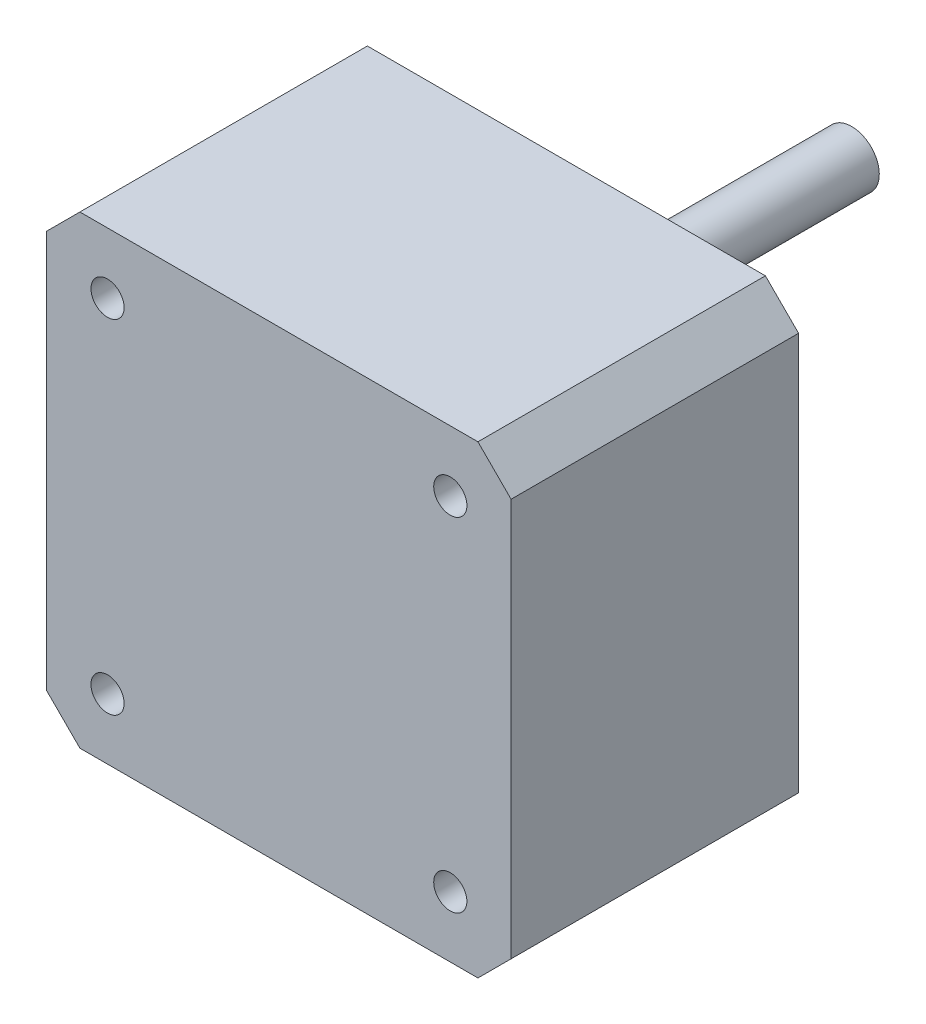
SolidWorks part; units mm, degrees
ref_plane "Front Plane" through (0, 0, 0) normal (0, 0, 1) x (1, 0, 0)
ref_plane "Top Plane" through (0, 0, 0) normal (0, 1, 0) x (1, 0, 0)
ref_plane "Right Plane" through (0, 0, 0) normal (1, 0, 0) x (0, 0, -1)
sketch "Sketch1" plane through (0, 0, 0) normal (0, 0, 1) x (1, 0, 0)
  line L1 (-21, 21) -> (21, 21)
  line L2 (-21, 21) -> (-21, -21)
  line L3 (-21, -21) -> (21, -21)
  line L4 (21, 21) -> (21, -21)
  line L5 (-21, 21) -> (21, -21) construction
  line L6 (-21, -21) -> (21, 21) construction
  point P0 (0, 0)
  dimension "D1" = 42
  dimension "D2" = 42
extrude "Boss-Extrude1" add sketch "Sketch1" along normal blind 26 contours L1 L4 L3 L2
chamfer "Chamfer1" distance 3 angle 45 4 edges at (21, -21, 13) (-21, -21, 13) (-21, 21, 13) (21, 21, 13)
sketch "Sketch4" plane through (0, 0, 0) normal (0, 0, -1) x (-1, 0, 0)
  circle A0 centre (0, 0) radius 11.25
  dimension "D1" = 22.5
extrude "Boss-Extrude2" add sketch "Sketch4" against normal blind 0.5
sketch "Sketch8" plane through (0, 0, 0) normal (0, 0, -1) x (-1, 0, 0)
  circle A4 centre (15.5, 15.5) radius 1.5
  circle A5 centre (-15.5, 15.5) radius 1.5
  circle A6 centre (-15.5, -15.5) radius 1.5
  circle A7 centre (15.5, -15.5) radius 1.5
  dimension "D1" = 31
  dimension "D2" = 31
  dimension "D4" = 3
  dimension "D3" = 15.5
  dimension "D5" = 15.5
extrude "Cut-Extrude4" cut sketch "Sketch8" against normal up to next
sketch "Sketch9" plane through (0, 0, 0) normal (0, 0, -1) x (-1, 0, 0)
  circle A0 centre (0, 0) radius 18.35
  dimension "D1" = 36.7
extrude "Cut-Extrude5" cut sketch "Sketch9" against normal blind 0.5
sketch "Sketch10" plane through (0, 0, 0.5) normal (0, 0, -1) x (-1, 0, 0)
  line L0 (18, 21) -> (-18, 21) construction
  circle A0 centre (0, 8.3) radius 8.9
  circle A3 centre (0, 8.3) radius 2.75
  dimension "D1" = 17.8
  dimension "D3" = 5.5
  dimension "D2" = 12.7
extrude "Boss-Extrude3" add sketch "Sketch10" along normal blind 3.5
sketch "Sketch11" plane through (0, 0, 0.5) normal (0, 0, -1) x (-1, 0, 0)
  line L0 (-1.6815, 6.45) -> (1.6815, 6.45)
  arc A0 (1.6815, 6.45) -> (-1.6815, 6.45) centre (0, 8.3) ccw
  dimension "D1" = 5
  dimension "D2" = 1.85
extrude "Boss-Extrude4" add sketch "Sketch11" along normal blind 26.3
fillet "Fillet1" radius 0.5 1 edges at (-8.9, 8.3, 0.5)
